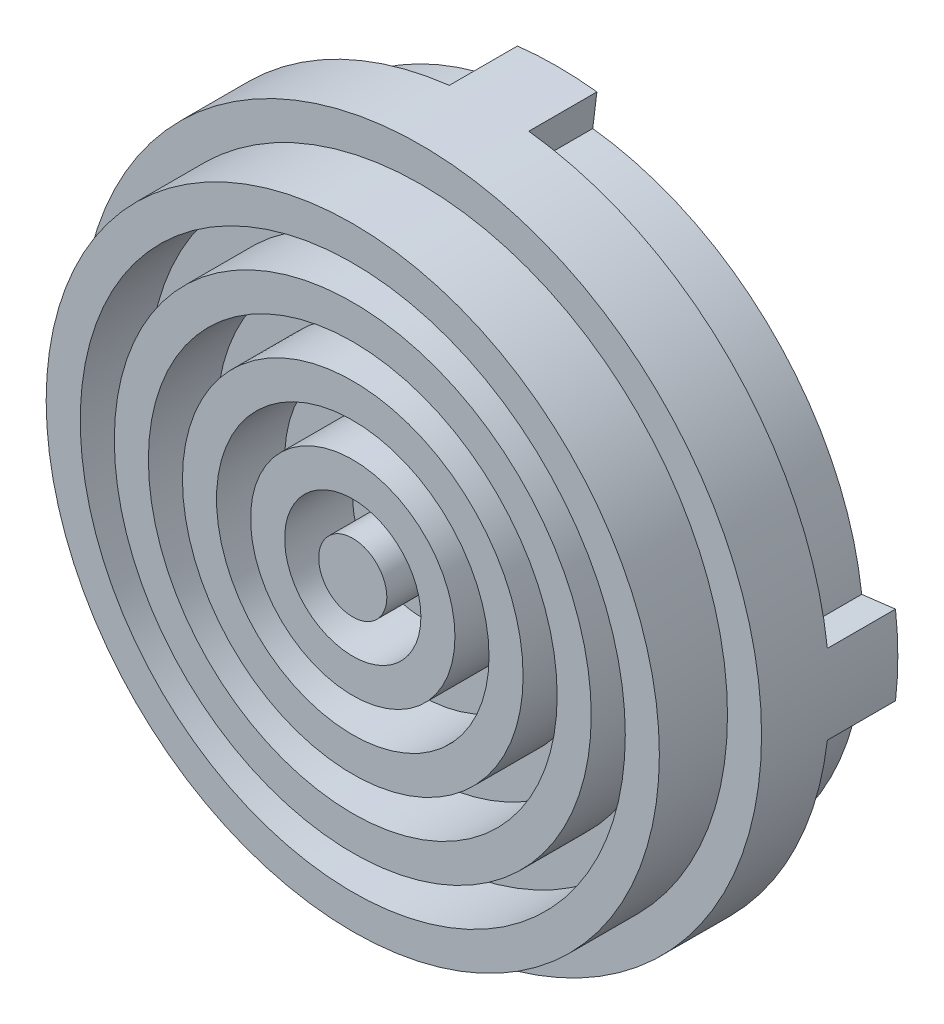
SolidWorks part; units mm, degrees
ref_plane "Front Plane" through (0, 0, 0) normal (0, 0, 1) x (1, 0, 0)
ref_plane "Top Plane" through (0, 0, 0) normal (0, 1, 0) x (1, 0, 0)
ref_plane "Right Plane" through (0, 0, 0) normal (1, 0, 0) x (0, 0, -1)
sketch "Sketch1" plane through (0, 0, 0) normal (0, 0, 1) x (1, 0, 0)
  circle A0 centre (0, 0) radius 150
  dimension "D1" = 300
extrude "Boss-Extrude1" add sketch "Sketch1" along normal blind 30
sketch "Sketch2" plane through (0, 0, 30) normal (0, 0, 1) x (1, 0, 0)
  circle A1 centre (0, 0) radius 120
  circle A2 centre (0, 0) radius 135
  circle A3 centre (0, 0) radius 135
  circle A4 centre (0, 0) radius 105
  circle A5 centre (0, 0) radius 90
  circle A6 centre (0, 0) radius 75
  circle A7 centre (0, 0) radius 60
  circle A8 centre (0, 0) radius 45
  circle A9 centre (0, 0) radius 30
  circle A10 centre (0, 0) radius 15
  dimension "D1" = 15
  dimension "D2" = 15
  dimension "D3" = 15
  dimension "D4" = 15
  dimension "D5" = 15
  dimension "D6" = 15
  dimension "D7" = 15
  dimension "D8" = 15
  dimension "D9" = 15
extrude "Boss-Extrude2" add sketch "Sketch2" along normal blind 30 contours A3 A1 | A4 A5 | A6 A7 | A8 A9 | A10
sketch "Sketch3" plane through (0, 0, 0) normal (0, 0, -1) x (-1, 0, 0)
  circle A0 centre (0, 0) radius 35
  circle A1 centre (0, 0) radius 75
  circle A2 centre (0, 0) radius 135
  circle A3 centre (0, 0) radius 15
  circle A4 centre (0, 0) radius 55
  circle A5 centre (0, 0) radius 115
  dimension "D1" = 70
  dimension "D2" = 150
  dimension "D3" = 270
  dimension "D4" = 20
extrude "Boss-Extrude3" add sketch "Sketch3" along normal blind 30 contours A2 A5 | A1 A4 | A0 A3
sketch "Sketch4" plane through (0, 0, 0) normal (0, 0, -1) x (-1, 0, 0)
  line L0 (0, 0) -> (0, 150) construction
  line L1 (-5.3473, 50) -> (5.3473, 50)
  line L2 (5.3473, 50) -> (17.5, 148.9757)
  line L3 (-5.3473, 50) -> (-17.5, 148.9757)
  line L4 (50, 5.3473) -> (148.9757, 17.5)
  line L5 (50, 5.3473) -> (50, -5.3473)
  line L6 (50, -5.3473) -> (148.9757, -17.5)
  line L7 (5.3473, -50) -> (17.5, -148.9757)
  line L8 (5.3473, -50) -> (-5.3473, -50)
  line L9 (-5.3473, -50) -> (-17.5, -148.9757)
  line L10 (-50, -5.3473) -> (-148.9757, -17.5)
  line L11 (-50, -5.3473) -> (-50, 5.3473)
  line L12 (-50, 5.3473) -> (-148.9757, 17.5)
  circle A0 centre (0, 0) radius 150 construction
  arc A1 (148.9757, -17.5) -> (148.9757, 17.5) centre (0, 0) ccw
  circle A2 centre (0, 0) radius 150
  arc A3 (17.5, 148.9757) -> (-17.5, 148.9757) centre (0, 0) ccw
  arc A4 (-17.5, -148.9757) -> (17.5, -148.9757) centre (0, 0) ccw
  arc A5 (-148.9757, 17.5) -> (-148.9757, -17.5) centre (0, 0) ccw
  point P8 (0, 50)
  point P27 (0, 0)
  dimension "D2" = 35
  dimension "D3" = 100
  dimension "D4" = 14
  dimension "D1" = 0
  dimension "D5" = 4
extrude "Boss-Extrude4" add sketch "Sketch4" along normal blind 30
equation "\"D2@Sketch2\"=\"D1@Sketch2\""
equation "\"D3@Sketch2\"=\"D1@Sketch2\""
equation "\"D4@Sketch2\"=\"D1@Sketch2\""
equation "\"D5@Sketch2\"=\"D1@Sketch2\""
equation "\"D6@Sketch2\"=\"D1@Sketch2\""
equation "\"D7@Sketch2\"=\"D1@Sketch2\""
equation "\"D8@Sketch2\"=\"D1@Sketch2\""
equation "\"D9@Sketch2\"=\"D1@Sketch2\""
